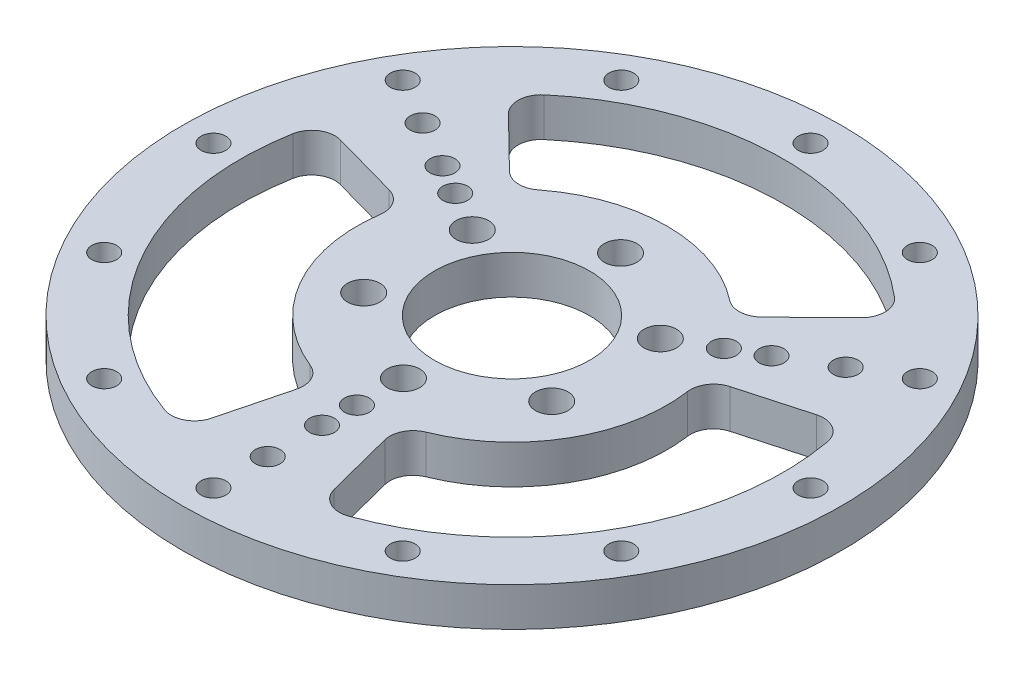
SolidWorks part; units mm, degrees
ref_plane "前视基准面" through (0, 0, 0) normal (0, 0, 1) x (1, 0, 0)
ref_plane "上视基准面" through (0, 0, 0) normal (0, 1, 0) x (1, 0, 0)
ref_plane "右视基准面" through (0, 0, 0) normal (1, 0, 0) x (0, 0, -1)
other "Configuration Table"
sketch "草图1" plane through (0, 0, 0) normal (0, 1, 0) x (1, 0, 0)
  line L0 (0, 42.5) -> (0, 0) construction
  line L1 (0, 0) -> (42.5, 0) construction
  line L2 (-33.342, 19.25) -> (0, 0) construction
  line L3 (-25, 24.4949) -> (-14.2857, 13.9971)
  line L4 (25, 24.4949) -> (14.2857, 13.9971)
  line L5 (-14.2857, 13.9971) -> (0, 0) construction
  line L6 (8.7132, -33.8981) -> (4.979, -19.3703)
  line L7 (33.7132, 9.4032) -> (19.2647, 5.3732)
  line L8 (-33.7132, 9.4032) -> (-19.2647, 5.3732)
  line L9 (-8.7132, -33.8981) -> (-4.979, -19.3703)
  circle A0 centre (0, 0) radius 10
  circle A1 centre (0, 0) radius 42.5
  circle A2 centre (0, 0) radius 24.5 construction
  circle A3 centre (0, 0) radius 20 construction
  circle A4 centre (0, 0) radius 31.5 construction
  circle A5 centre (0, 0) radius 38.5 construction
  circle A6 centre (0, 0) radius 14 construction
  circle A7 centre (0, 14) radius 2.1
  circle A8 centre (12.1244, 7) radius 2.1
  circle A9 centre (12.1244, -7) radius 2.1
  circle A10 centre (0, -14) radius 2.1
  circle A11 centre (-12.1244, -7) radius 2.1
  circle A12 centre (-12.1244, 7) radius 2.1
  circle A13 centre (0, 38.5) radius 1.6
  circle A14 centre (19.25, 33.342) radius 1.6
  circle A15 centre (33.342, 19.25) radius 1.6
  circle A16 centre (38.5, 0) radius 1.6
  circle A17 centre (33.342, -19.25) radius 1.6
  circle A18 centre (19.25, -33.342) radius 1.6
  circle A19 centre (0, -38.5) radius 1.6
  circle A20 centre (-19.25, -33.342) radius 1.6
  circle A21 centre (-33.342, -19.25) radius 1.6
  circle A22 centre (-38.5, 0) radius 1.6
  circle A23 centre (-33.342, 19.25) radius 1.6
  circle A24 centre (-19.25, 33.342) radius 1.6
  circle A25 centre (-27.2798, 15.75) radius 1.6
  circle A26 centre (-21.2176, 12.25) radius 1.6
  circle A27 centre (-17.3205, 10) radius 1.6
  circle A37 centre (27.2798, 15.75) radius 1.6
  circle A38 centre (21.2176, 12.25) radius 1.6
  circle A39 centre (17.3205, 10) radius 1.6
  circle A49 centre (0, -31.5) radius 1.6
  circle A50 centre (0, -24.5) radius 1.6
  circle A51 centre (0, -20) radius 1.6
  circle A61 centre (-15.75, 27.2798) radius 1.6 [skipped]
  circle A62 centre (-12.25, 21.2176) radius 1.6 [skipped]
  circle A63 centre (-10, 17.3205) radius 1.6 [skipped]
  circle A64 centre (15.75, 27.2798) radius 1.6 [skipped]
  circle A65 centre (12.25, 21.2176) radius 1.6 [skipped]
  circle A66 centre (10, 17.3205) radius 1.6 [skipped]
  circle A67 centre (-31.5, 0) radius 1.6 [skipped]
  circle A68 centre (-24.5, 0) radius 1.6 [skipped]
  circle A69 centre (-20, 0) radius 1.6 [skipped]
  circle A70 centre (-27.2798, -15.75) radius 1.6 [skipped]
  circle A71 centre (-21.2176, -12.25) radius 1.6 [skipped]
  circle A72 centre (-17.3205, -10) radius 1.6 [skipped]
  circle A73 centre (-12.25, -21.2176) radius 1.6 [skipped]
  circle A74 centre (-15.75, -27.2798) radius 1.6 [skipped]
  circle A75 centre (-10, -17.3205) radius 1.6 [skipped]
  circle A76 centre (10, -17.3205) radius 1.6 [skipped]
  circle A77 centre (12.25, -21.2176) radius 1.6 [skipped]
  circle A78 centre (15.75, -27.2798) radius 1.6 [skipped]
  circle A79 centre (17.3205, -10) radius 1.6 [skipped]
  circle A80 centre (21.2176, -12.25) radius 1.6 [skipped]
  circle A81 centre (27.2798, -15.75) radius 1.6 [skipped]
  circle A82 centre (24.5, 0) radius 1.6 [skipped]
  circle A83 centre (20, 0) radius 1.6 [skipped]
  circle A84 centre (31.5, 0) radius 1.6 [skipped]
  circle A85 centre (0, 31.5) radius 1.6 [skipped]
  circle A86 centre (0, 24.5) radius 1.6 [skipped]
  circle A87 centre (0, 20) radius 1.6 [skipped]
  circle A88 centre (0, 0) radius 35 construction
  arc A89 (-14.2857, 13.9971) -> (14.2857, 13.9971) centre (0, 0) cw
  arc A90 (-25, 24.4949) -> (25, 24.4949) centre (0, 0) cw
  arc A91 (33.7132, 9.4032) -> (8.7132, -33.8981) centre (0, 0) cw
  arc A92 (19.2647, 5.3732) -> (4.979, -19.3703) centre (0, 0) cw
  arc A93 (-8.7132, -33.8981) -> (-33.7132, 9.4032) centre (0, 0) cw
  arc A94 (-4.979, -19.3703) -> (-19.2647, 5.3732) centre (0, 0) cw
  point P25 (0, 0)
  point P50 (0, 0)
  point P72 (0, 0)
  point P123 (0, 0)
  dimension "D1" = 20
  dimension "D2" = 85
  dimension "D3" = 77
  dimension "D4" = 63
  dimension "D5" = 49
  dimension "D6" = 40
  dimension "D7" = 28
  dimension "D8" = 4.2
  dimension "D10" = 3.2
  dimension "D13" = 70
  dimension "D14" = 25
  dimension "D9" = 6
  dimension "D11" = 12
  dimension "D12" = 12
  dimension "D15" = 3
extrude "凸台-拉伸1" add sketch "草图1" along normal blind 5
fillet "圆角1" radius 3 12 edges at (25, 2.5, -24.4949) (14.2857, 2.5, -13.9971) (-14.2857, 2.5, -13.9971) (-25, 2.5, -24.4949) (19.2647, 2.5, -5.3732) (4.979, 2.5, 19.3703) (33.7132, 2.5, -9.4032) (8.7132, 2.5, 33.8981) (-8.7132, 2.5, 33.8981) (-4.979, 2.5, 19.3703) (-19.2647, 2.5, -5.3732) (-33.7132, 2.5, -9.4032)
